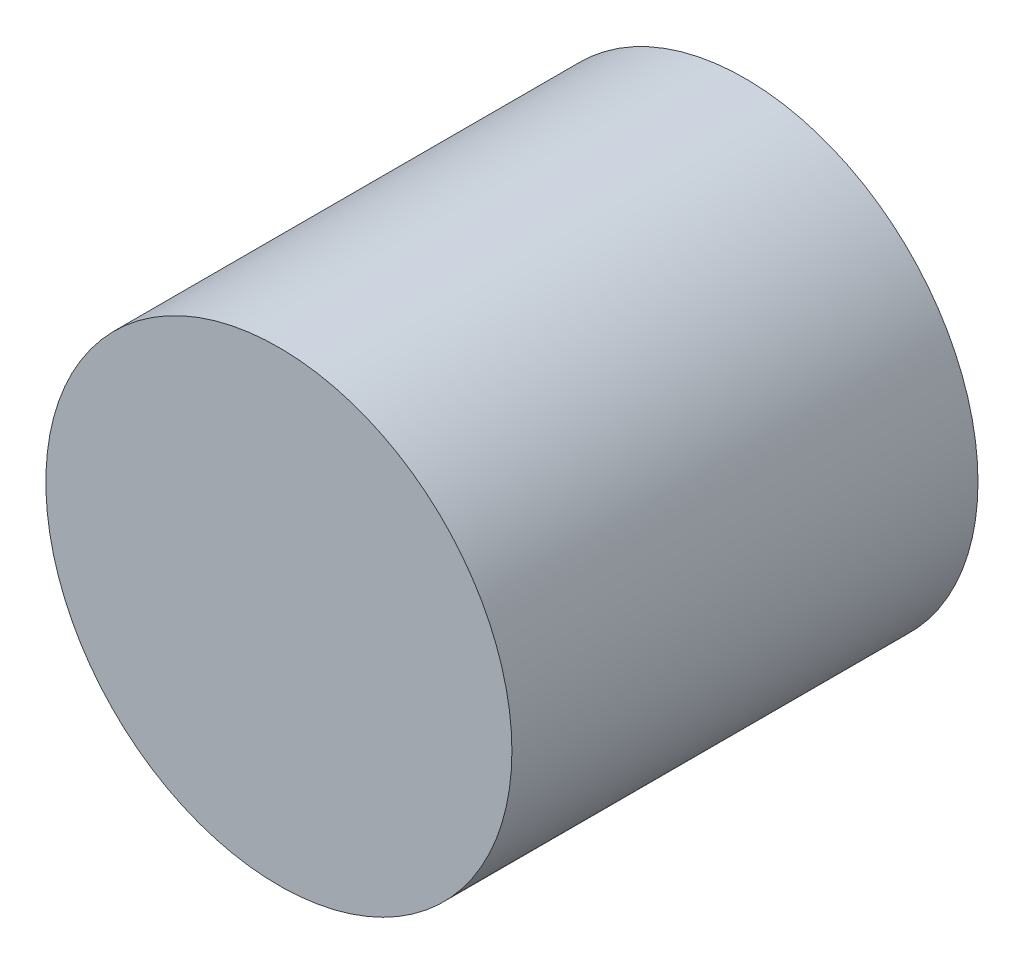
SolidWorks part; units mm, degrees
ref_plane "Piano frontale" through (0, 0, 0) normal (0, 0, 1) x (1, 0, 0)
ref_plane "Piano superiore" through (0, 0, 0) normal (0, 1, 0) x (1, 0, 0)
ref_plane "Piano destro" through (0, 0, 0) normal (1, 0, 0) x (0, 0, -1)
sketch "Schizzo1" plane through (0, 0, 0) normal (0, 0, 1) x (1, 0, 0)
  circle A0 centre (0, 0) radius 12.5
  dimension "D1" = 25
extrude "Estrusione-Estrusione1" add sketch "Schizzo1" along normal blind 25 contours A0
